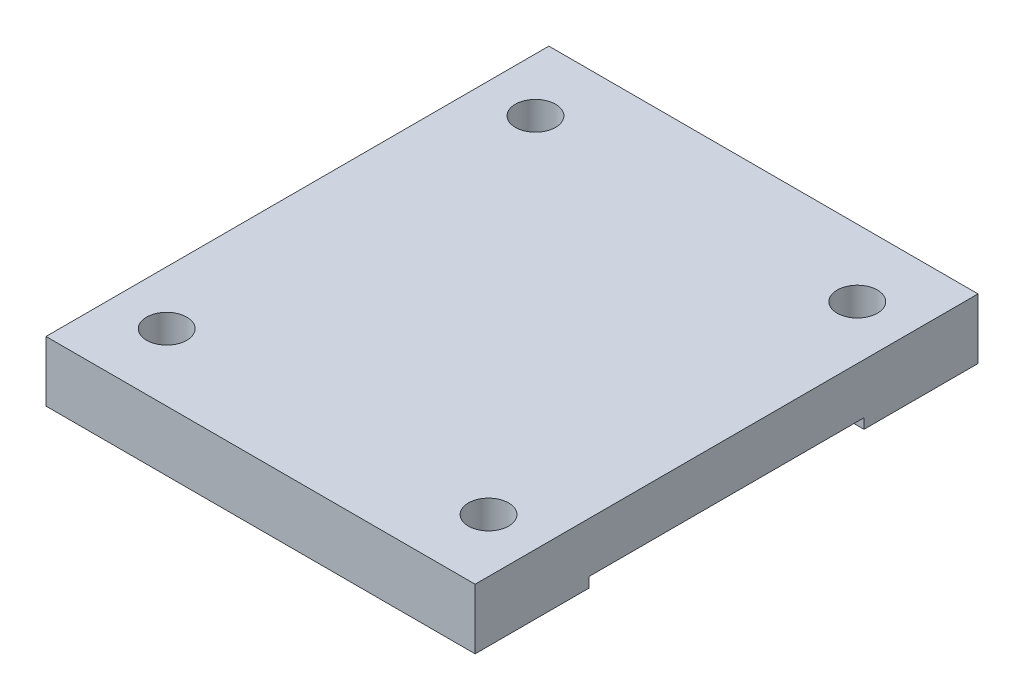
SolidWorks part; units mm, degrees
ref_plane "Front" through (0, 0, 0) normal (0, 0, 1) x (1, 0, 0)
ref_plane "Top" through (0, 0, 0) normal (0, 1, 0) x (1, 0, 0)
ref_plane "Right" through (0, 0, 0) normal (1, 0, 0) x (0, 0, -1)
sketch "Sketch1" plane through (0, 0, 0) normal (0, 1, 0) x (1, 0, 0)
  line L0 (-8.7703, 0) -> (82.7333, 0) construction
  line L1 (0, 37.5) -> (64, 37.5)
  line L2 (0, 37.5) -> (0, -37.5)
  line L3 (0, -37.5) -> (64, -37.5)
  line L4 (64, 37.5) -> (64, -37.5)
  dimension "D1" = 75
  dimension "D2" = 64
extrude "Boss-Extrude1" add sketch "Sketch1" along normal blind 9
sketch "Sketch2" plane through (0, 0, 0) normal (0, -1, 0) x (1, 0, 0)
  line L0 (0, -37.5) -> (0, 37.5) construction
  line L1 (0, 20.5) -> (64, 20.5)
  line L2 (0, 20.5) -> (0, -20.5)
  line L3 (0, -20.5) -> (64, -20.5)
  line L4 (64, 20.5) -> (64, -20.5)
  line L5 (64, 37.5) -> (64, -37.5) construction
  line L6 (-4.0183, 0) -> (69.237, 0) construction
  dimension "D1" = 41
extrude "Cut-Extrude1" cut sketch "Sketch2" against normal blind 1.5
hole_wizard "Ø6.0 (6) Diameter Hole1" positions "Sketch4" profile "Sketch3" hole size "Ø6.0" standard "JIS" end condition through all
sketch "Sketch4" plane through (0, 9, 0) normal (0, 1, 0) x (-1, 0, 0)
  line L0 (4.7856, 0) -> (-67.6572, 0) construction
  line L1 (0, -37.5) -> (0, 37.5) construction
  point P0 (-8, 27.5)
  point P1 (-8, -27.5)
  point P3 (-56, -27.5)
  point P5 (-56, 27.5)
  dimension "D1" = 55
  dimension "D2" = 48
  dimension "D3" = 8
sketch "Sketch3" plane through (8, 9, 27.5) normal (1, 0, 0) x (0, 0, 1)
  line L0 (0, 0) -> (0, 9)
  line L1 (0, 9) -> (3, 9)
  line L2 (3, 9) -> (3, 0)
  line L5 (3, 0) -> (0, 0)
  line L11 (0, -6.35) -> (0, 107.95) construction
  dimension "Thru Hole Dia." = 6
  dimension "Thru Hole Depth" = 9
